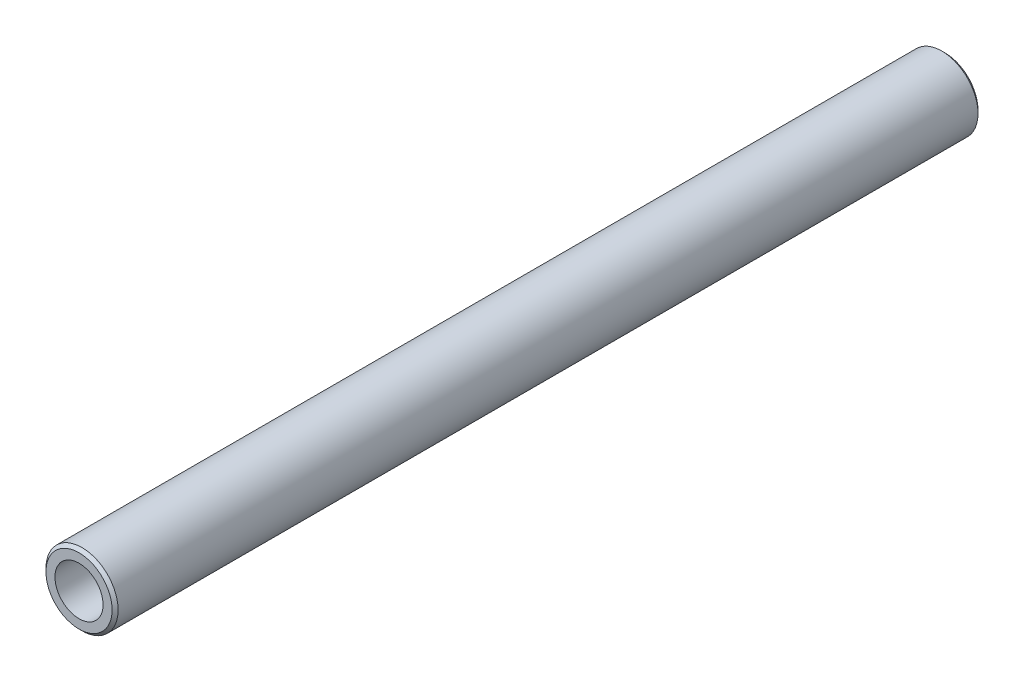
SolidWorks part; units mm, degrees
ref_plane "Plano frontal" through (0, 0, 0) normal (0, 0, 1) x (1, 0, 0)
ref_plane "Plano superior" through (0, 0, 0) normal (0, 1, 0) x (1, 0, 0)
ref_plane "Plano direito" through (0, 0, 0) normal (1, 0, 0) x (0, 0, -1)
sketch "Esboço1" plane through (0, 0, 0) normal (0, 0, 1) x (1, 0, 0)
  circle A0 centre (0, 0) radius 3
  dimension "D1" = 6
extrude "Ressalto-extrusão1" add sketch "Esboço1" along normal mid plane 72
chamfer "Chanfro1" distance 0.25 angle 45 2 edges at (3, 0, -36) (3, 0, 36)
sketch "Esboço2" plane through (0, 0, 36) normal (0, 0, 1) x (1, 0, 0)
  circle A0 centre (0, 0) radius 2
  dimension "D1" = 4
extrude "Corte-extrusão1" cut sketch "Esboço2" against normal blind 16
cosmetic thread "Representação de rosca1" parameters "D2"=5
mirror "Espelhar1" about plane through (0, 0, 0) normal (0, 0, 1) of "Corte-extrusão1"
